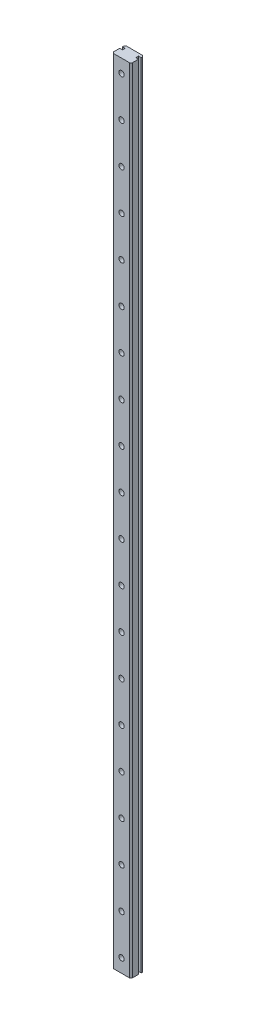
SolidWorks part; units mm, degrees
material "AISI 304"
ref_plane "前视基准面" through (0, 0, 0) normal (0, 0, 1) x (1, 0, 0)
ref_plane "上视基准面" through (0, 0, 0) normal (0, 1, 0) x (1, 0, 0)
ref_plane "右视基准面" through (0, 0, 0) normal (1, 0, 0) x (0, 0, -1)
other "Configuration Table"
sketch "草图1" plane through (0, 0, 0) normal (0, 1, 0) x (1, 0, 0)
  line L0 (0, 0) -> (0, 7.157) construction
  line L1 (-3.5, -2.4) -> (3.5, -2.4)
  line L2 (-3.5, -2.4) -> (-3.5, 2.4)
  line L3 (-3.5, 2.4) -> (3.5, 2.4)
  line L4 (3.5, -2.4) -> (3.5, 2.4)
  line L5 (-3.5, -2.4) -> (3.5, 2.4) construction
  line L6 (-3.5, 2.4) -> (3.5, -2.4) construction
  line L7 (3.5, 1.4) -> (2.5, 1.4)
  line L8 (2.5, 1.4) -> (2.5, 0.4)
  line L9 (2.5, 0.4) -> (3.5, 0.4)
  line L10 (-2.5, 0.4) -> (-3.5, 0.4)
  line L11 (-2.5, 1.4) -> (-2.5, 0.4)
  line L12 (-3.5, 1.4) -> (-2.5, 1.4)
  point P0 (0, 0)
  dimension "D1" = 7
  dimension "D2" = 4.8
  dimension "D3" = 1
  dimension "D4" = 1
  dimension "D5" = 1
extrude "凸台-拉伸1" add sketch "草图1" along normal blind 295 contours L2 L12 L11 L10 L1 L4 L9 L8 L7 L3
sketch "草图2" plane through (0, 0, -2.4) normal (0, 0, -1) x (-1, 0, 0)
  line L0 (3.5, 0) -> (-3.5, 0) construction
  line L1 (-3.5, 295) -> (-3.5, 0) construction
  circle A0 centre (0, 5) radius 1
  circle A1 centre (0, 20) radius 1
  circle A2 centre (0, 35) radius 1
  circle A3 centre (0, 50) radius 1
  circle A4 centre (0, 65) radius 1
  circle A5 centre (0, 80) radius 1
  circle A6 centre (0, 95) radius 1
  circle A7 centre (0, 110) radius 1
  circle A8 centre (0, 125) radius 1
  circle A9 centre (0, 140) radius 1
  circle A10 centre (0, 155) radius 1
  circle A11 centre (0, 170) radius 1
  circle A12 centre (0, 185) radius 1
  circle A13 centre (0, 200) radius 1
  circle A14 centre (0, 215) radius 1
  circle A15 centre (0, 230) radius 1
  circle A16 centre (0, 245) radius 1
  circle A17 centre (0, 260) radius 1
  circle A18 centre (0, 275) radius 1
  circle A19 centre (0, 290) radius 1
  dimension "D1" = 2
  dimension "D2" = 5
  dimension "D5" = 15
  dimension "D3" = 3.5
  dimension "D4" = 20
extrude "切除-拉伸1" cut sketch "草图2" against normal blind 10
chamfer "倒角1" distance 0.5 angle 45 4 edges at (-3.5, 147.5, 2.4) (3.5, 147.5, 2.4) (-3.5, 147.5, -2.4) (3.5, 147.5, -2.4)
sketch "草图3" plane through (0, 0, -2.4) normal (0, 0, -1) x (-1, 0, 0)
  circle A0 centre (0, 5) radius 2.3833
  circle A1 centre (0, 20) radius 2.3833
  circle A2 centre (0, 35) radius 2.3833
  circle A3 centre (0, 50) radius 2.3833
  circle A4 centre (0, 65) radius 2.3833
  circle A5 centre (0, 80) radius 2.3833
  circle A6 centre (0, 95) radius 2.3833
  circle A7 centre (0, 110) radius 2.3833
  circle A8 centre (0, 125) radius 2.3833
  circle A9 centre (0, 140) radius 2.3833
  circle A10 centre (0, 155) radius 2.3833
  circle A11 centre (0, 170) radius 2.3833
  circle A12 centre (0, 185) radius 2.3833
  circle A13 centre (0, 200) radius 2.3833
  circle A14 centre (0, 215) radius 2.3833
  circle A15 centre (0, 230) radius 2.3833
  circle A16 centre (0, 245) radius 2.3833
  circle A17 centre (0, 260) radius 2.3833
  circle A18 centre (0, 275) radius 2.3833
  circle A19 centre (0, 290) radius 2.3833
  dimension "D1" = 4.7666
  dimension "D3" = 15
  dimension "D2" = 20
extrude "切除-拉伸2" cut sketch "草图3" against normal blind 1
